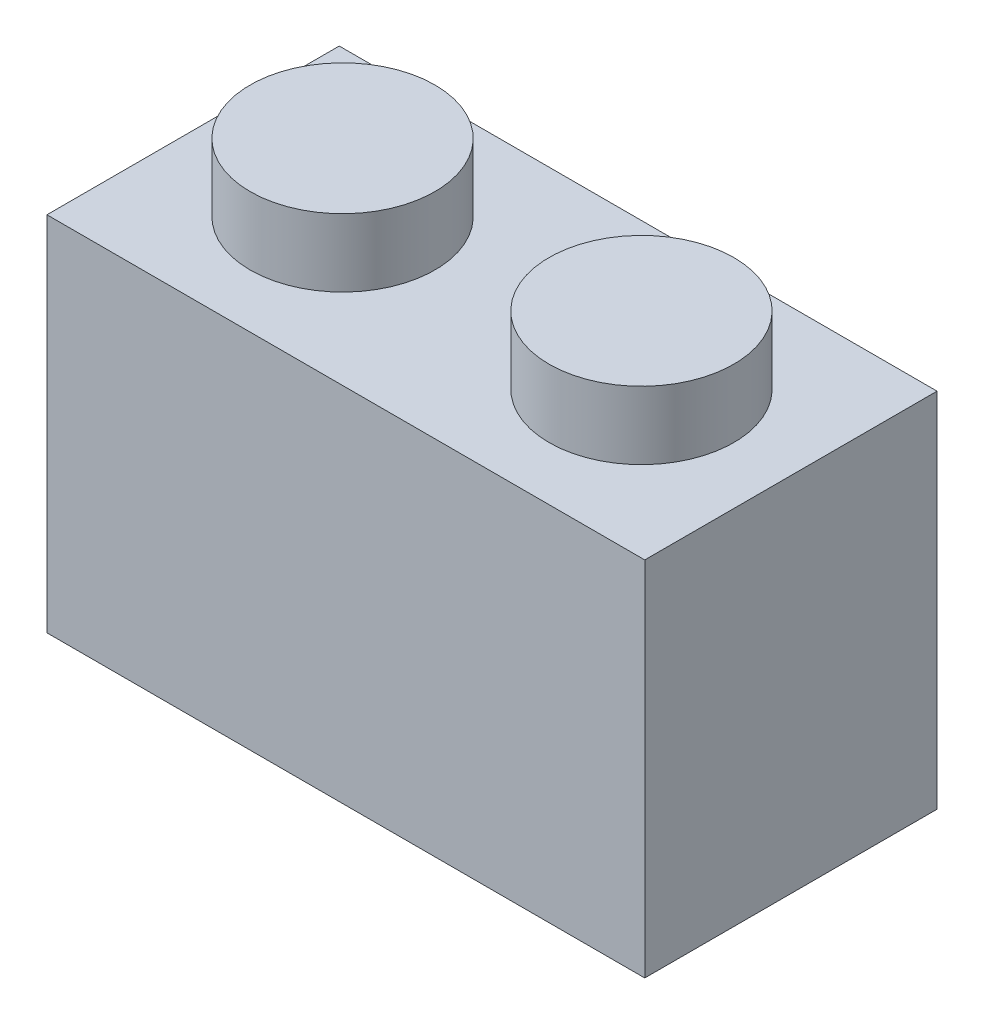
SolidWorks part; units mm, degrees
ref_plane "Front Plane" through (0, 0, 0) normal (0, 0, 1) x (1, 0, 0)
ref_plane "Top Plane" through (0, 0, 0) normal (0, 1, 0) x (1, 0, 0)
ref_plane "Right Plane" through (0, 0, 0) normal (1, 0, 0) x (0, 0, -1)
sketch "Sketch1" plane through (0, 0, 0) normal (0, 1, 0) x (1, 0, 0)
  line L1 (-7.925, 3.875) -> (7.925, 3.875)
  line L2 (-7.925, 3.875) -> (-7.925, -3.875)
  line L3 (-7.925, -3.875) -> (7.925, -3.875)
  line L4 (7.925, 3.875) -> (7.925, -3.875)
  line L5 (-7.925, 3.875) -> (7.925, -3.875) construction
  line L6 (-7.925, -3.875) -> (7.925, 3.875) construction
  point P0 (0, 0)
  dimension "D1" = 15.85
  dimension "D2" = 7.75
extrude "Boss-Extrude1" add sketch "Sketch1" against normal blind 9.6
sketch "Sketch2" plane through (0, 0, 0) normal (0, 1, 0) x (1, 0, 0)
  line L0 (7.925, 3.875) -> (-7.925, 3.875) construction
  line L1 (-7.925, 3.875) -> (-7.925, -3.875) construction
  line L2 (0, 6.3123) -> (0, -4.7696) construction
  circle A0 centre (-3.9625, 0) radius 2.45
  circle A2 centre (3.9625, 0) radius 2.45
  dimension "D2" = 4.9
  dimension "D3" = 3.9625
  dimension "D1" = 3.875
extrude "Boss-Extrude2" add sketch "Sketch2" along normal blind 1.8
shell "Shell1" thickness 1.5
